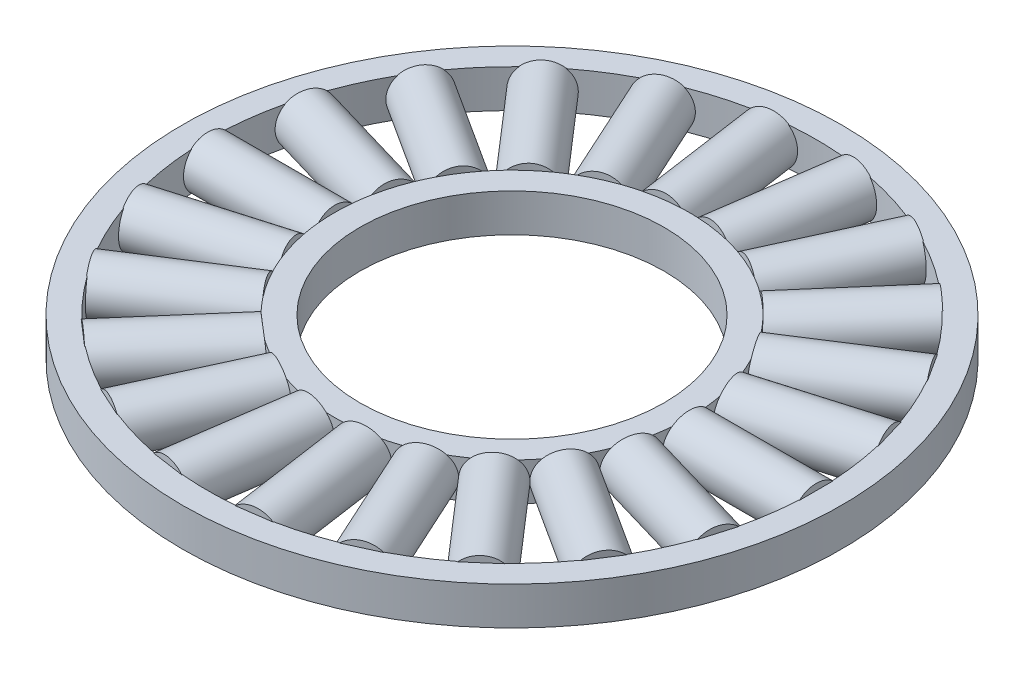
SolidWorks part; units mm, degrees
ref_plane "前视基准面" through (0, 0, 0) normal (0, 0, 1) x (1, 0, 0)
ref_plane "上视基准面" through (0, 0, 0) normal (0, 1, 0) x (1, 0, 0)
ref_plane "右视基准面" through (0, 0, 0) normal (1, 0, 0) x (0, 0, -1)
sketch "草图1" plane through (0, 0, 0) normal (0, 1, 0) x (1, 0, 0)
  circle A0 centre (0, 0) radius 6
  circle A1 centre (0, 0) radius 13
  circle A2 centre (0, 0) radius 12
  circle A3 centre (0, 0) radius 7
  dimension "D1" = 26
  dimension "D2" = 12
  dimension "D3" = 1
  dimension "D4" = 1
extrude "凸台-拉伸1" add sketch "草图1" along normal blind 1.5 contours A1 A2 | A3 A0
ref_plane "基准面1" through (-12, 0, 0) normal (1, 0, 0) x (0, 0, -1)
sketch "草图2" plane through (-12, 0, 0) normal (1, 0, 0) x (0, 0, -1)
  line L0 (13, 0.75) -> (-13, 0.75) construction
  line L1 (13, 0) -> (13, 1.5) construction
  line L2 (-13, 1.5) -> (-13, 0) construction
  circle A0 centre (0, 0.75) radius 1
  dimension "D1" = 2
extrude "凸台-拉伸2" add sketch "草图2" along normal up to surface (5.0718 mm away)
pattern_circular "阵列(圆周)1" count 22 over 360 about axis through (0, 0, 0) along (0, 1, 0) of "凸台-拉伸2"
